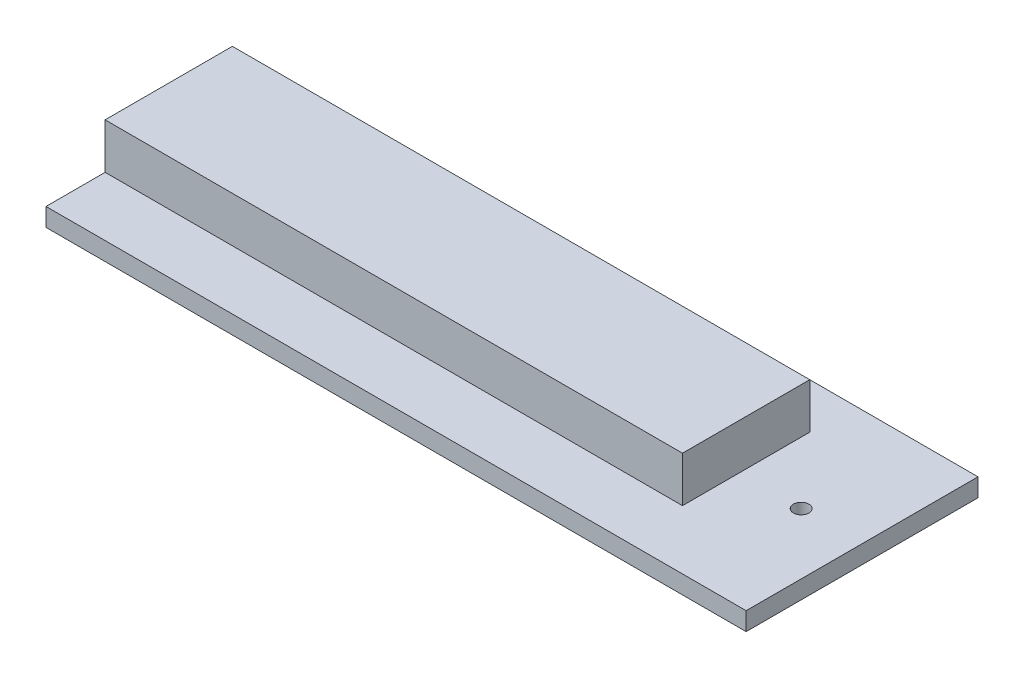
SolidWorks part; units mm, degrees
ref_plane "Front Plane" through (0, 0, 0) normal (0, 0, 1) x (1, 0, 0)
ref_plane "Top Plane" through (0, 0, 0) normal (0, 1, 0) x (1, 0, 0)
ref_plane "Right Plane" through (0, 0, 0) normal (1, 0, 0) x (0, 0, -1)
sketch "Sketch1" plane through (0, 0, 0) normal (0, 1, 0) x (1, 0, 0)
  line L0 (0, 25.5) -> (154, 25.5) construction
  line L1 (0, 0) -> (154, 0)
  line L2 (0, 0) -> (0, 51)
  line L3 (0, 51) -> (154, 51)
  line L4 (154, 0) -> (154, 51)
  line L5 (77, 51) -> (77, 0) construction
  circle A0 centre (77, 25.5) radius 1.7
  circle A1 centre (13.4, 25.5) radius 1.7
  circle A2 centre (140.6, 25.5) radius 1.7
  dimension "D4" = 3.4
  dimension "D1" = 154
  dimension "D2" = 51
  dimension "D3" = 13.4
extrude "Boss-Extrude1" add sketch "Sketch1" along normal blind 4
sketch "Sketch2" plane through (0, 4, 0) normal (0, 1, 0) x (1, 0, 0)
  line L0 (0, 13) -> (127, 13)
  line L1 (0, 51) -> (0, 0) construction
  line L2 (127, 13) -> (127, 41)
  line L3 (127, 41) -> (0, 41)
  line L4 (0, 41) -> (0, 13)
  line L5 (154, 0) -> (154, 51) construction
  line L6 (154, 51) -> (0, 51) construction
  line L7 (0, 0) -> (154, 0) construction
  dimension "D1" = 27
  dimension "D2" = 10
  dimension "D3" = 13
extrude "Boss-Extrude2" add sketch "Sketch2" along normal blind 10
